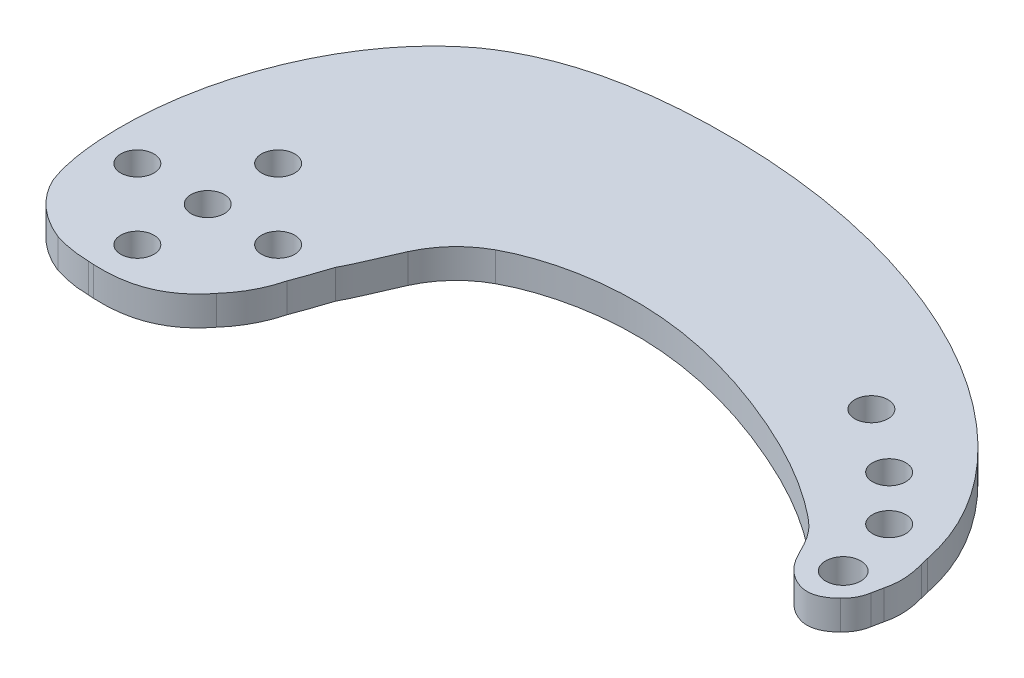
SolidWorks part; units mm, degrees
ref_plane "前视基准面" through (0, 0, 0) normal (0, 0, 1) x (1, 0, 0)
ref_plane "上视基准面" through (0, 0, 0) normal (0, 1, 0) x (1, 0, 0)
ref_plane "右视基准面" through (0, 0, 0) normal (1, 0, 0) x (0, 0, -1)
other "Configuration Table"
sketch "草图1" plane through (0, 0, 0) normal (0, 1, 0) x (1, 0, 0)
  line L0 (0, 0) -> (65, 0) construction
  line L1 (0, 0) -> (0, -7.2) construction
  line L2 (0, -7.2) -> (0, 7.2) construction
  line L3 (0, 7.2) -> (0, 0) construction
  line L4 (0, 0) -> (-7.2, 0) construction
  line L5 (-7.2, 0) -> (7.2, 0) construction
  line L6 (-11.2, 0) -> (68.4, 0)
  line L7 (-11.2, 0) -> (68.4, 0) construction
  line L8 (68.4, 0) -> (28.6, 0) construction
  line L9 (61.6, 0) -> (11.2, 0) construction
  line L10 (11.2, 0) -> (36.4, 0) construction
  line L11 (0, -11.2) -> (61.6, 0) construction
  line L12 (61.6, 0) -> (30.8, -5.6) construction
  line L13 (0, -11.2) -> (65, -3.4) construction
  line L14 (65, -3.4) -> (32.5, -7.3) construction
  line L15 (65, -3.4) -> (1.7026, 11.0698) construction
  line L16 (1.7026, 11.0698) -> (33.3513, 3.8349) construction
  circle A0 centre (0, 0) radius 1.7
  circle A1 centre (7.2, 0) radius 1.7
  circle A2 centre (0, -7.2) radius 1.7
  circle A3 centre (-7.2, 0) radius 1.7
  circle A4 centre (0, 7.2) radius 1.7
  circle A5 centre (0, 0) radius 11.2
  circle A6 centre (65, 0) radius 1.7
  circle A7 centre (65, 0) radius 3.4
  arc A8 (-11.2, 0) -> (68.4, 0) centre (28.6, 0) cw
  arc A9 (11.2, 0) -> (61.6, 0) centre (36.4, 0) cw
  arc A10 (61.6, 0) -> (3.9424, 10.4832) centre (30.8, -5.6) ccw
  arc A11 (65, -3.4) -> (1.7026, 11.0698) centre (33.3513, 3.8349) ccw
  dimension "D6" = 3.4
  dimension "D7" = 3.4
  dimension "D8" = 3.4
  dimension "D9" = 3.4
  dimension "D10" = 3.4
  dimension "D11" = 22.4
  dimension "D12" = 3.4
  dimension "D13" = 6.8
  dimension "D1" = 65
  dimension "D2" = 7.2
  dimension "D3" = 14.4
  dimension "D4" = 7.2
  dimension "D5" = 14.4
extrude "凸台-拉伸1" add sketch "草图1" along normal blind 3 contours L6 A5 A3 A0 A1 A4 | L6 A5 A1 A0 A3 A2 | A7 A11 A5 A10 A9 | A11 A7 A8 A5 | A9 A10 A5 | A10 A9 | A7 A11 A6 L6 | A11 A7 L6 A6 | A11 A6 L6 A7 | A6 A11 A7 L6 | L6 A10 A9
sketch "草图2" plane through (0, 0, 0) normal (0, 1, 0) x (1, 0, 0)
  line L0 (68.8496, -5.3501) -> (79.4183, 26.7989)
  line L1 (79.4183, 26.7989) -> (41.5102, 45.7213)
  line L2 (41.5102, 45.7213) -> (-3.7389, 40.2154)
  line L3 (-3.7389, 40.2154) -> (-19.4379, 8.7648)
  line L4 (-19.4379, 8.7648) -> (-13.9911, 0)
  line L5 (-13.9911, 0) -> (-11.2, 0)
  line L6 (11.2, 0) -> (61.6, 0)
  arc A0 (68.4, 0) -> (-11.2, 0) centre (28.6, 0) ccw construction
  spline S0 degree 3 poles (-11.2, 0) (-10.9857, 9.512) (-6.7904, 26.8834) (30.2577, 38.2179) (69.3708, 18.7501) (68.8496, -5.3501) knots 0 0 0 0 0.267986 0.373432 1 1 1 1
  spline S1 degree 3 poles (11.2, 0) (14.9072, 24.8789) (54.0365, 12.1796) (61.6, 0) knots 0 0 0 0 1 1 1 1
extrude "切除-拉伸3" cut sketch "草图2" along normal blind 3 contours L5 S0 L0 L1 L2 L3 L4 | L6 S1
sketch "草图3" plane through (0, 0, 0) normal (0, 1, 0) x (1, 0, 0)
  line L0 (65, 1.7) -> (65, -1.7) construction
  arc A0 (61.6, 0) -> (68.4, 0) centre (65, 0) ccw construction
  circle A1 centre (65, 0) radius 1.7 construction
  circle A2 centre (65, 0) radius 1.7
  spline S0 degree 3 poles (5.6259, 36.5086) (10.8061, -6.7566) (16.5714, 16.8024) (35.7888, 14.2527) (51.2496, 9.4424) (60.2383, 2.7416) (64.7704, -5.1874) (69.2066, -0.0025) (68.3961, 6.3767) (55.9681, 24.9502) (5.6259, 36.5086) (10.8061, -6.7566) (16.5714, 16.8024) knots -0.49861 -0.434329 -0.078808 0 0.081161 0.198318 0.331057 0.406548 0.438622 0.470697 0.50139 0.565671 0.921192 1 1.081161 1.198318 1.331057 only from (11.2, 0) to (11.2, 0)
  spline S1 degree 3 poles (11.2, 0) (14.9072, 24.8789) (54.0365, 12.1796) (61.6, 0) knots 0 0 0 0 1 1 1 1 construction
extrude "凸台-拉伸3" add sketch "草图3" along normal blind 3
fillet "圆角9" radius 10 2 edges at (17.0596, 1.5, -10.6629) (11.2, 1.5, 0)
fillet "圆角10" radius 10 2 edges at (68.4, 1.5, 0) (61.6, 1.5, 0)
fillet "圆角14" radius 20 1 edges at (59.2538, 1.5, -16.1636)
sketch "草图4" plane through (0, 0, 0) normal (0, 1, 0) x (1, 0, 0)
  line L0 (5.2054, -8.2635) -> (-0.4561, -10.2991)
  line L1 (-0.4561, -10.2991) -> (-8.7258, -3.4925)
  line L2 (-8.7258, -3.4925) -> (-9.6163, 1.6601)
  line L3 (-9.6163, 1.6601) -> (-4.0517, 17.4826)
  line L4 (-4.0517, 17.4826) -> (31.1592, 24.1153)
  line L5 (31.1592, 24.1153) -> (64.8102, 6.0493)
  line L6 (64.8102, 6.0493) -> (67.2275, 0)
  line L7 (67.2275, 0) -> (68.3633, -0.4984)
  arc A0 (-11.2, 0) -> (10.9952, -2.1318) centre (0, 0) ccw construction
  spline S0 degree 3 poles (68.3633, -0.4984) (69.5327, 7.7303) (60.7385, 20.6272) (41.0242, 30.6364) (20.6209, 33.8057) (-5.2599, 29.9907) (-13.0727, 6.8588) (-10.2682, -6.4009) (-7.7755, -9.6175) (-6.4668, -9.9226) (-2.2619, -11.5691) (2.3358, -11.7732) (5.2054, -8.2635) knots 0 0 0 0 0.167184 0.308916 0.466623 0.613186 0.82769 0.890098 0.902059 0.911312 0.918106 1 1 1 1
extrude "凸台-拉伸4" add sketch "草图4" along normal blind 3
sketch "草图6" plane through (0, 0, 0) normal (0, 1, 0) x (1, 0, 0)
  line L0 (6.1981, 30.7694) -> (-15.2014, 29.1144)
  line L1 (-15.2014, 29.1144) -> (-14.1745, -13.8901)
  line L2 (-14.1745, -13.8901) -> (0, -13.5516)
  line L3 (0, -13.5516) -> (-1.0708, -11.1487)
  spline S0 degree 3 poles (-1.0708, -11.1487) (-4.6321, -11.3725) (-9.7437, -8.3658) (-10.906, -2.8062) (-12.5638, 11.2276) (-5.8916, 27.3023) (6.1981, 30.7694) knots 0 0 0 0 0.203093 0.264366 0.313017 1 1 1 1
  spline S1 degree 3 poles (-10.8971, -2.5872) (-10.5448, -4.6323) (-9.7232, -7.1042) (-7.7755, -9.6175) (-6.4668, -9.9226) (-4.3924, -10.7349) (-2.5621, -11.1419) (-1.0708, -11.1487) knots 0.845974 0.845974 0.845974 0.845974 0.890098 0.902059 0.911312 0.918106 0.950375 0.950375 0.950375 0.950375 construction
  spline S2 degree 3 poles (68.2809, 5.0052) (67.2637, 10.8617) (59.1043, 21.4569) (41.0242, 30.6364) (20.6266, 33.8048) (5.4538, 31.57) (0.0138, 27.688) knots 0.03868 0.03868 0.03868 0.03868 0.167184 0.308916 0.466623 0.613062 0.613062 0.613062 0.613062 construction
extrude "切除-拉伸4" cut sketch "草图6" along normal blind 3
sketch "草图7" plane through (0, 3, 0) normal (0, 1, 0) x (1, 0, 0)
  line L0 (67.2676, -2.5334) -> (62.7967, -1.5444)
  line L1 (62.7967, -1.5444) -> (59.283, 6.9625)
  line L2 (59.283, 6.9625) -> (25.5896, 20.1617)
  line L3 (25.5896, 20.1617) -> (9.9827, 8.0209)
  line L4 (9.9827, 8.0209) -> (9.9827, 0)
  line L5 (9.9827, 0) -> (6.1386, -6.8237)
  line L6 (6.1386, -6.8237) -> (-0.5501, -10.3603)
  line L7 (-0.5501, -10.3603) -> (-1.0708, -11.1487)
  arc A0 (-1.0708, -11.1487) -> (10.9952, -2.1318) centre (0, 0) ccw construction
  arc A1 (65.1241, -3.3977) -> (68.3633, -0.4984) centre (65, 0) ccw construction
  spline S0 degree 3 poles (-1.0708, -11.1487) (7.8127, -11.9196) (10.9618, -2.8561) (14.7813, 9.2423) (28.5331, 15.182) (44.1776, 11.5506) (55.3323, 5.5463) (59.4573, 2.1343) (60.7284, 0.393) (61.5845, -1.8281) (63.3373, -3.3442) (65.4369, -3.8983) (66.7101, -3.1454) (67.2676, -2.5334) knots 0 0 0 0 0.226109 0.317464 0.429096 0.705434 0.851539 0.872298 0.892425 0.926476 0.954706 0.970023 1 1 1 1
extrude "凸台-拉伸6" add sketch "草图7" against normal blind 3
fillet "圆角20" radius 10 1 edges
fillet "圆角21" radius 10 1 edges at (68.2809, 1.5, -5.0052)
sketch "草图8" plane through (0, 0, 0) normal (0, 1, 0) x (1, 0, 0)
  line L0 (65, 1.7) -> (65, -1.7) construction
  line L1 (65, -1.7) -> (65, 0) construction
  circle A0 centre (65, 0) radius 1.7 construction
  circle A1 centre (65, 0) radius 1.8
  dimension "D1" = 3.6
extrude "切除-拉伸5" cut sketch "草图8" along normal blind 3
sketch "草图9" plane through (0, 0, 0) normal (0, 1, 0) x (1, 0, 0)
  line L0 (63.2, 0) -> (63.2, 6.5) construction
  line L1 (63.2, 6.5) -> (58.6038, 11.0962) construction
  line L2 (58.6038, 11.0962) -> (52.1102, 15.7688) construction
  circle A0 centre (65, 0) radius 1.8 construction
  circle A1 centre (63.2, 6.5) radius 1.7
  circle A2 centre (58.6038, 11.0962) radius 1.7
  circle A3 centre (52.1102, 15.7688) radius 1.7
  dimension "D2" = 3.4
  dimension "D4" = 3.4
  dimension "D6" = 3.4
  dimension "D1" = 6.5
  dimension "D3" = 6.5
  dimension "D5" = 8
extrude "切除-拉伸6" cut sketch "草图9" along normal blind 10
